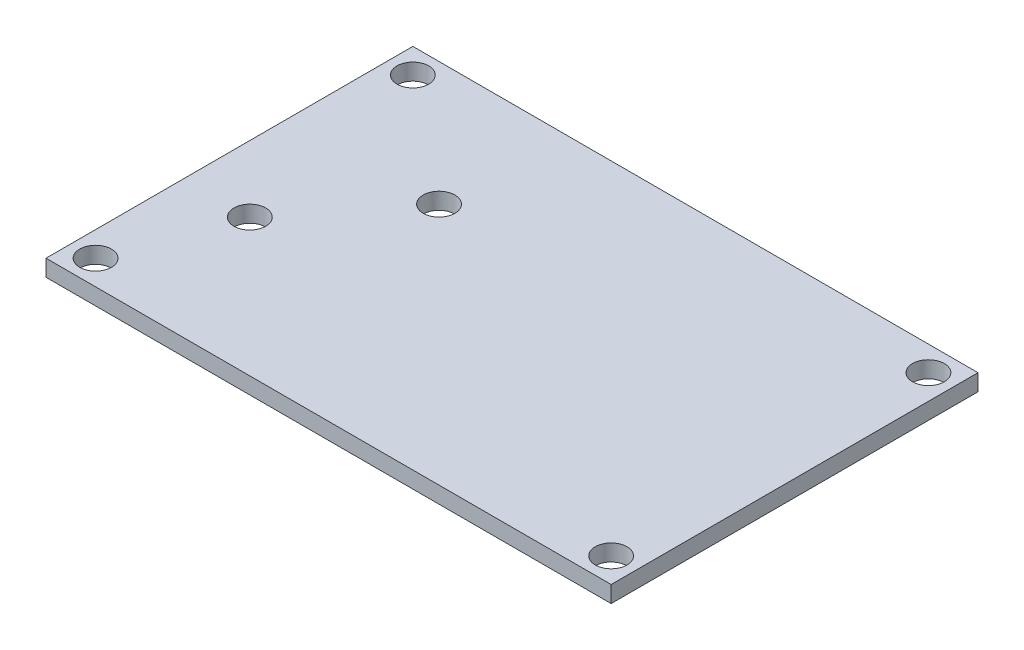
SolidWorks part; units mm, degrees
material "Leaded Commercial Bronze"
ref_plane "Front Plane" through (0, 0, 0) normal (0, 0, 1) x (1, 0, 0)
ref_plane "Top Plane" through (0, 0, 0) normal (0, 1, 0) x (1, 0, 0)
ref_plane "Right Plane" through (0, 0, 0) normal (1, 0, 0) x (0, 0, -1)
sketch "Sketch1" plane through (0, 0, 0) normal (0, 1, 0) x (1, 0, 0)
  line L1 (28.5, -18.5) -> (-28.5, -18.5)
  line L2 (28.5, -18.5) -> (28.5, 18.5)
  line L3 (28.5, 18.5) -> (-28.5, 18.5)
  line L4 (-28.5, -18.5) -> (-28.5, 18.5)
  line L5 (28.5, -18.5) -> (-28.5, 18.5) construction
  line L6 (28.5, 18.5) -> (-28.5, -18.5) construction
  point P0 (0, 0)
  dimension "D1" = 37
  dimension "D2" = 57
extrude "Boss-Extrude1" add sketch "Sketch1" along normal blind 1.67
sketch "Sketch2" plane through (0, 1.67, 0) normal (0, 1, 0) x (1, 0, 0)
  line L0 (-28.5, 18.5) -> (-28.5, -18.5) construction
  line L1 (-28.5, -18.5) -> (28.5, -18.5) construction
  circle A0 centre (-26, -16) radius 1.6
  circle A1 centre (-26, 16) radius 1.6
  circle A2 centre (26, -16) radius 1.6
  circle A3 centre (26, 16) radius 1.6
  circle A4 centre (-13.4, 6.04) radius 1.6
  circle A5 centre (-21.81, -4.63) radius 1.6
  dimension "D1" = 3.2
  dimension "D6" = 13.87
  dimension "D2" = 2.5
  dimension "D3" = 2.5
  dimension "D4" = 34.5
  dimension "D5" = 54.5
  dimension "D7" = 6.69
  dimension "D8" = 15.1
  dimension "D9" = 24.54
extrude "Cut-Extrude1" cut sketch "Sketch2" against normal up to surface (1.67 mm away) up to face at (0, 0, 0)
sketch "Sketch3" plane through (0, 0, 0) normal (0, -1, 0) x (1, 0, 0)
  circle A0 centre (-26, -16) radius 1.6 construction
  point P0 (10.5233, -16.9684)
  point P1 (-10.1607, -16.9684)
  point P2 (-10.947, 16.3721)
  point P3 (11.6591, 16.3721)
  dimension "D1" = 15.053
  dimension "D2" = 15.8393
  dimension "D3" = 36.5233
  dimension "D4" = 37.6591
  dimension "D5" = 32.3721
  dimension "D6" = 0.9684
